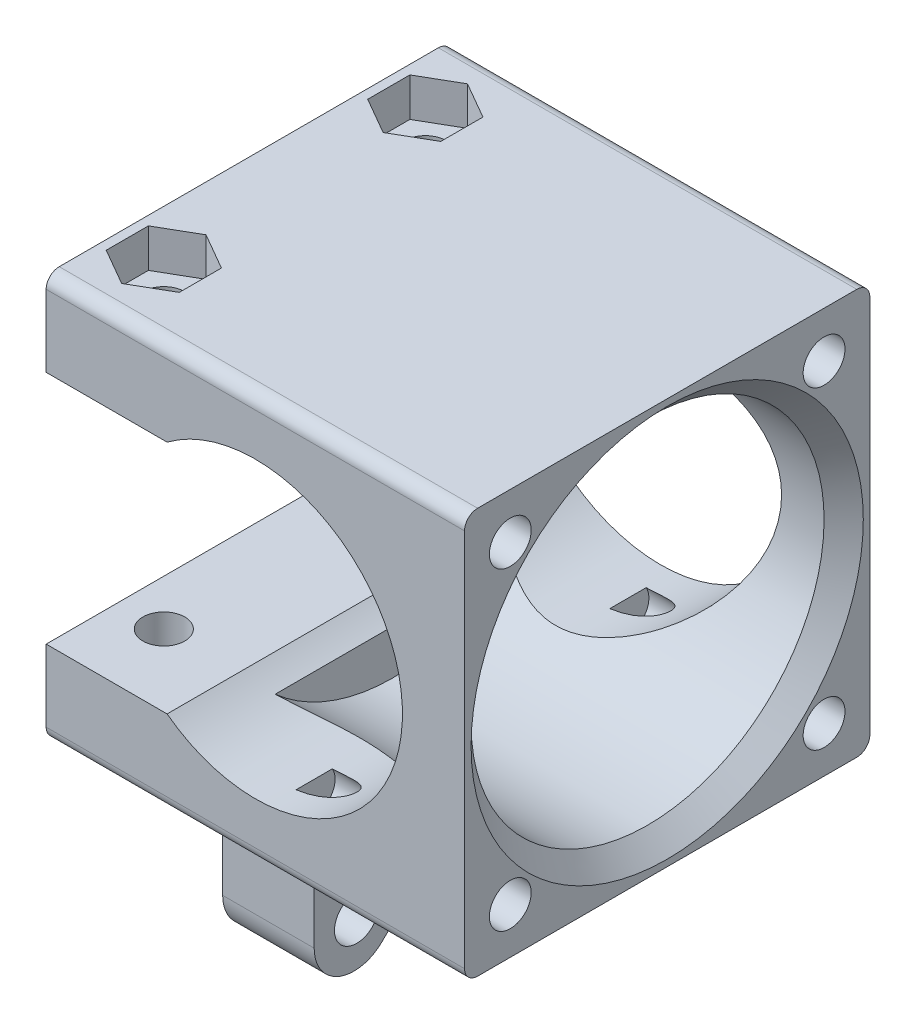
SolidWorks part; units mm, degrees
material "ABS"
ref_plane "Front Plane" through (0, 0, 0) normal (0, 0, 1) x (1, 0, 0)
ref_plane "Top Plane" through (0, 0, 0) normal (0, 1, 0) x (1, 0, 0)
ref_plane "Right Plane" through (0, 0, 0) normal (1, 0, 0) x (0, 0, -1)
sketch "Sketch1" plane through (0, 0, 0) normal (1, 0, 0) x (0, 0, -1)
  line L1 (-31, -15.5) -> (0, -15.5)
  line L2 (-31, -15.5) -> (-31, 15.5)
  line L3 (-31, 15.5) -> (0, 15.5)
  line L4 (0, -15.5) -> (0, 15.5)
  dimension "D1" = 31
  dimension "D2" = 31
extrude "Boss-Extrude1" add sketch "Sketch1" against normal mid plane 32
fillet "Fillet1" radius 1 4 edges at (0, 15.5, 0) (0, -15.5, 31) (0, -15.5, 0) (0, 15.5, 31)
sketch "Sketch2" plane through (16, 0, 0) normal (1, 0, 0) x (0, 0, -1)
  line L0 (-15.5, 15.5) -> (-15.5, -15.5) construction
  line L1 (-1, 15.5) -> (-30, 15.5) construction
  line L2 (-30, -15.5) -> (-1, -15.5) construction
  circle A0 centre (-15.5, 0) radius 13.5
  dimension "D1" = 27
extrude "Cut-Extrude1" cut sketch "Sketch2" against normal blind 21
sketch "Sketch3" plane through (16, 0, 0) normal (1, 0, 0) x (0, 0, -1)
  line L0 (-27.5, -12) -> (-27.5, 12) construction
  line L1 (-27.5, 12) -> (-3.5, 12) construction
  line L2 (-15.5, 12) -> (-15.5, 0) construction
  line L3 (-15.5, 0) -> (-27.5, 0) construction
  circle A0 centre (-27.5, 12) radius 1.6
  circle A1 centre (-3.5, 12) radius 1.6
  circle A2 centre (-3.5, -12) radius 1.6
  circle A3 centre (-27.5, -12) radius 1.6
  dimension "D1" = 3.2
  dimension "D2" = 24
extrude "Cut-Extrude2" cut sketch "Sketch3" against normal blind 15
sketch "Sketch4" plane through (0, 0, 31) normal (0, 0, 1) x (1, 0, 0)
  line L0 (-6.75, 9) -> (-16, 9)
  line L1 (-16, 14.5) -> (-16, -14.5) construction
  line L2 (-16, 9) -> (-16, -9)
  line L3 (-16, -9) -> (-6.75, -9)
  line L4 (16, 14.5) -> (16, -14.5) construction
  arc A0 (-6.75, -9) -> (-6.75, 9) centre (0, 0) ccw
  dimension "D1" = 11.25
  dimension "D2" = 16
  dimension "D3" = 18
extrude "Cut-Extrude3" cut sketch "Sketch4" against normal through all
sketch "Sketch5" plane through (0, 15.5, 0) normal (0, 1, 0) x (1, 0, 0)
  line L0 (-12.5, -5.5) -> (-12.5, -25.5) construction
  line L1 (-16, -15.5) -> (-12.5, -15.5) construction
  line L2 (-16, -1) -> (-16, -30) construction
  circle A0 centre (-12.5, -5.5) radius 1.6
  circle A1 centre (-12.5, -25.5) radius 1.6
  dimension "D1" = 3.2
  dimension "D2" = 20
  dimension "D3" = 3.5
extrude "Cut-Extrude4" cut sketch "Sketch5" against normal through all
sketch "Sketch6" plane through (0, 15.5, 0) normal (0, 1, 0) x (1, 0, 0)
  line L1 (-12.5, -8.7254) -> (-9.7067, -7.1127)
  line L2 (-9.7067, -7.1127) -> (-9.7067, -3.8873)
  line L3 (-9.7067, -3.8873) -> (-12.5, -2.2746)
  line L4 (-12.5, -2.2746) -> (-15.2933, -3.8873)
  line L5 (-15.2933, -3.8873) -> (-15.2933, -7.1127)
  line L6 (-15.2933, -7.1127) -> (-12.5, -8.7254)
  line L7 (-9.7067, -27.1127) -> (-9.7067, -23.8873)
  line L8 (-9.7067, -23.8873) -> (-12.5, -22.2746)
  line L9 (-12.5, -22.2746) -> (-15.2933, -23.8873)
  line L10 (-15.2933, -23.8873) -> (-15.2933, -27.1127)
  line L11 (-15.2933, -27.1127) -> (-12.5, -28.7254)
  line L12 (-12.5, -28.7254) -> (-9.7067, -27.1127)
  circle A0 centre (-12.5, -5.5) radius 2.7933 construction
  circle A1 centre (-12.5, -25.5) radius 2.7933 construction
  dimension "D1" = 5.5866
extrude "Cut-Extrude5" cut sketch "Sketch6" against normal blind 2.95
sketch "Sketch7" plane through (0, -15.5, 0) normal (0, -1, 0) x (1, 0, 0)
  circle A0 centre (-12.5, 25.5) radius 2.85
  circle A1 centre (-12.5, 5.5) radius 2.85
  dimension "D1" = 5.7
extrude "Cut-Extrude6" cut sketch "Sketch7" against normal blind 2.95
sketch "Sketch8" plane through (16, 0, 0) normal (1, 0, 0) x (0, 0, -1)
  line L0 (-30, -15.5) -> (-30, -19.894)
  line L1 (-24.8452, -22.0873) -> (-18, -15.5)
  line L2 (-30, -15.5) -> (-1, -15.5) construction
  line L3 (-18, -15.5) -> (-30, -15.5)
  line L4 (-31, 14.5) -> (-31, -14.5) construction
  arc A0 (-30, -19.894) -> (-24.8452, -22.0873) centre (-26.956, -19.894) ccw
  dimension "D1" = 13
  dimension "D2" = 1
extrude "Boss-Extrude2" add sketch "Sketch8" against normal blind 7 from offset 12.5 offset against normal yes
sketch "Sketch9" plane through (3.5, 0, 0) normal (1, 0, 0) x (0, 0, -1)
  circle A0 centre (-26.75, -19.5) radius 1.7
extrude "Cut-Extrude7" cut sketch "Sketch9" against normal through all
chamfer "Chamfer1" distance 1.5 angle 45 1 edges at (16, 0, 2)
